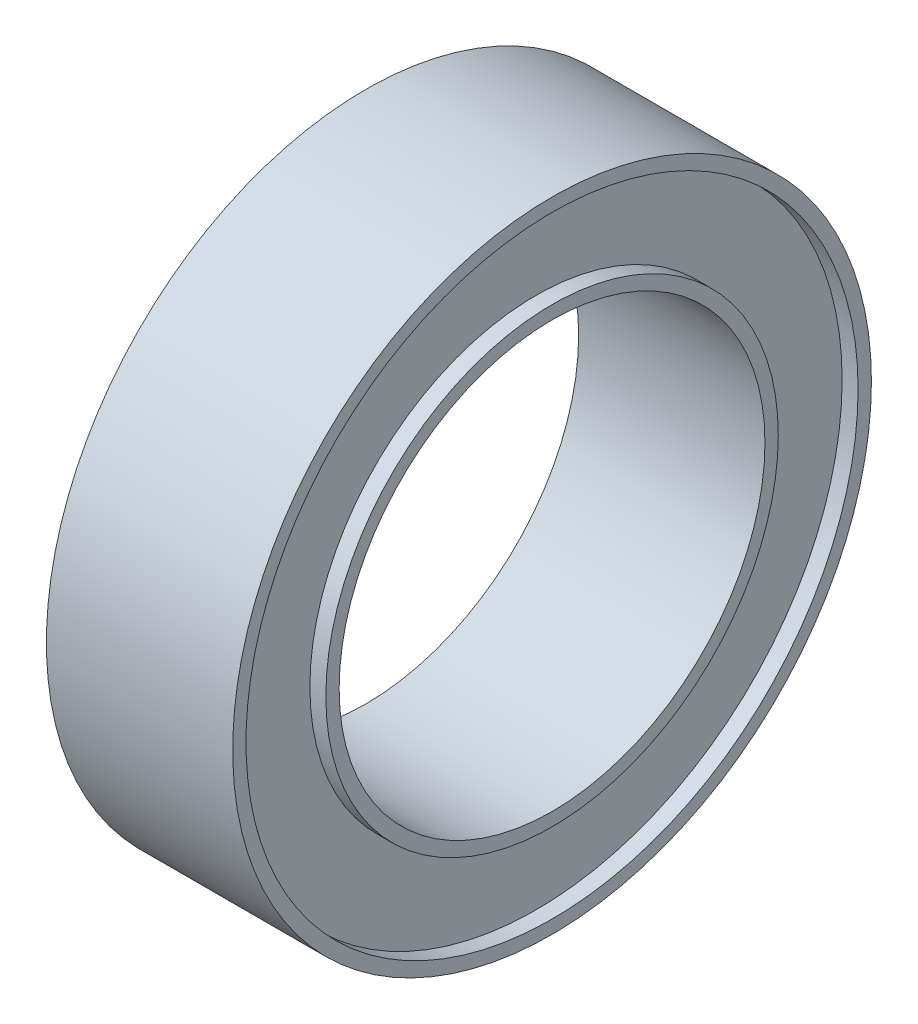
SolidWorks part; units mm, degrees
ref_plane "Front Plane" through (0, 0, 0) normal (0, 0, 1) x (1, 0, 0)
ref_plane "Top Plane" through (0, 0, 0) normal (0, 1, 0) x (1, 0, 0)
ref_plane "Right Plane" through (0, 0, 0) normal (1, 0, 0) x (0, 0, -1)
sketch "Sketch1" plane through (0, 0, 0) normal (1, 0, 0) x (0, 0, -1)
  circle A0 centre (0, 0) radius 6
  dimension "D1" = 12
extrude "Boss-Extrude1" add sketch "Sketch1" along normal mid plane 3.5
sketch "Sketch2" plane through (1.75, 0, 0) normal (1, 0, 0) x (0, 0, -1)
  circle A0 centre (0, 0) radius 4
  dimension "D1" = 8
extrude "Cut-Extrude1" cut sketch "Sketch2" against normal up to next
sketch "Sketch3" plane through (1.75, 0, 0) normal (1, 0, 0) x (0, 0, -1)
  circle A0 centre (0, 0) radius 4.25
  circle A1 centre (0, 0) radius 5.75
  dimension "D1" = 8.5
  dimension "D2" = 11.5
extrude "Cut-Extrude2" cut sketch "Sketch3" against normal blind 0.3
mirror "Mirror1" about plane through (0, 0, 0) normal (1, 0, 0) of "Cut-Extrude2"
